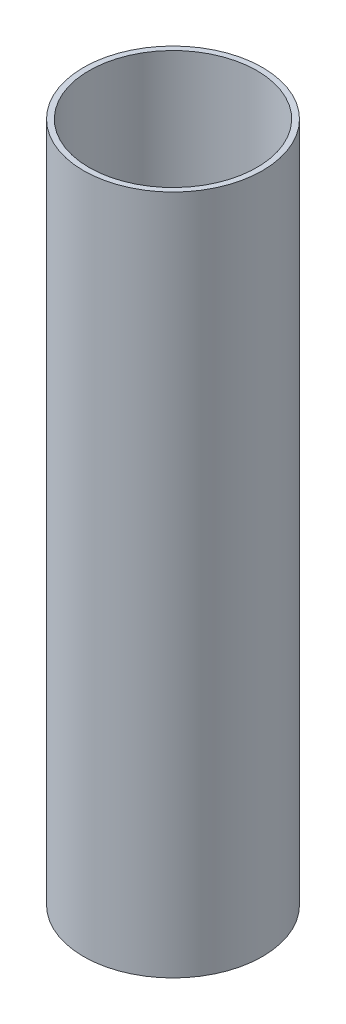
SolidWorks part; units mm, degrees
ref_plane "前视基准面" through (0, 0, 0) normal (0, 0, 1) x (1, 0, 0)
ref_plane "上视基准面" through (0, 0, 0) normal (0, 1, 0) x (1, 0, 0)
ref_plane "右视基准面" through (0, 0, 0) normal (1, 0, 0) x (0, 0, -1)
other "Configuration Table"
sketch "草图6" plane through (0, 0, 0) normal (1, 0, 0) x (0, 0, -1)
  line L1 (0, 0) -> (9.2, 0)
  line L2 (0, 0) -> (0, -70)
  line L3 (0, -70) -> (9.2, -70)
  line L4 (9.2, 0) -> (9.2, -70)
  dimension "D1" = 9.2
  dimension "D2" = 70
revolve "旋转2" add sketch "草图6" angle 360 about L2
sketch "草图9" plane through (0, 0, 0) normal (0, 1, 0) x (1, 0, 0)
  circle A0 centre (0, 0) radius 8.6322
extrude "切除-拉伸1" cut sketch "草图9" against normal through all
hole_wizard "M8x1.0 螺纹孔1" positions "3D草图1" profile "草图8" tap size "M8x1.0" standard "GB"
sketch3d "3D草图1"
  line L0 (0, 0, -7.75) -> (0, 0, 7.75) construction
  circle A0 centre (0, -50, 0) radius 5.5 construction
  point P0 (0, 0, 1.5941)
  point P4 (0, -50, 0)
  point P7 (0, -44.5, 0)
  dimension "D1" = 0
sketch "草图8" plane through (0, -50, 0) normal (1, 0, 0) x (0, 0, -1)
  line L0 (0, 0) -> (0, 42.3133)
  line L1 (0, 42.3133) -> (3.85, 40)
  line L2 (3.85, 40) -> (3.85, 0.175)
  line L3 (3.85, 0.175) -> (4.025, 0)
  line L5 (4.025, 0) -> (0, 0)
  line L6 (-3.85, 0.175) -> (-4.025, 0) construction
  line L10 (0, 42.3133) -> (-3.85, 40) construction
  line L11 (0, -6.35) -> (0, 107.95) construction
  dimension "螺纹孔钻头直径" = 7.7
  dimension "螺纹孔钻头深度" = 40
  dimension "近端锥形沉头孔直径" = 8.05
  dimension "近端锥形沉头孔角度" = 90
  dimension "导头角度" = 118
cosmetic thread "孔螺纹线8" parameters "D1"=16, "D2"=8
thread "螺纹线1" pitch 1 start angle 0, offset 0, length 60, pitch 1, diameter 7.7
ref_plane "基准面1" through (3.85, -50, 0) normal (0, 0, 1) x (1, 0, 0)
sketch "螺纹线轮廓1" plane through (3.85, -50, 0) normal (0, 0, 1) x (1, 0, 0)
  line L0 (0, 0) -> (0, 1) construction
  line L1 (0, 0) -> (0.5413, 0.3125)
  line L2 (0.5413, 0.3125) -> (0.5413, 0.4375)
  line L3 (0.5413, 0.4375) -> (0, 0.75)
  line L4 (0.5413, 0.375) -> (0, 0.375) construction
  line L11 (0, 0) -> (0, 0.75)
  point P2 (0, 0)
  dimension "Pitch" = 1
  dimension "Profile_Angle" = 60
  dimension "Profile_Land" = 0.125
  dimension "Profile_Height" = 0.5413
